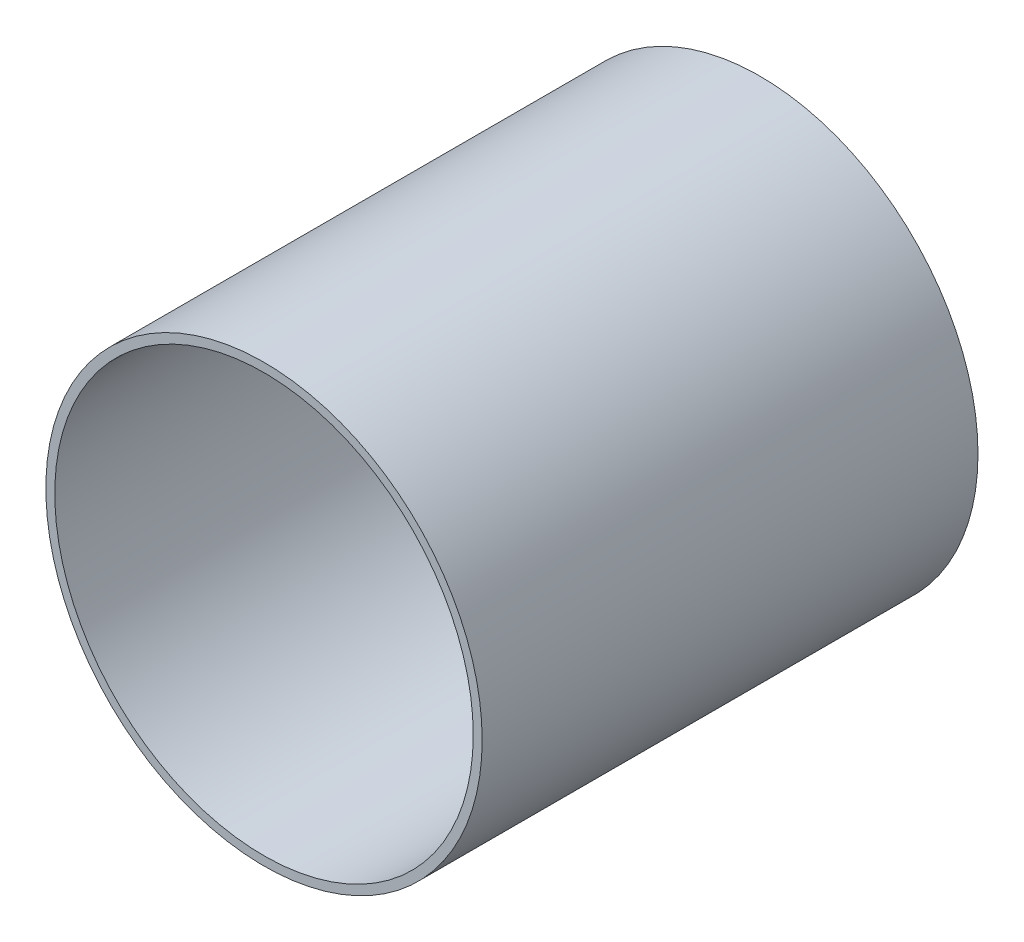
SolidWorks part; units mm, degrees
ref_plane "Front Plane" through (0, 0, 0) normal (0, 0, 1) x (1, 0, 0)
ref_plane "Top Plane" through (0, 0, 0) normal (0, 1, 0) x (1, 0, 0)
ref_plane "Right Plane" through (0, 0, 0) normal (1, 0, 0) x (0, 0, -1)
sketch "Sketch1" plane through (0, 0, 0) normal (0, 0, 1) x (1, 0, 0)
  circle A0 centre (0, 0) radius 10.55
  circle A1 centre (0, 0) radius 11
  dimension "D1" = 22
  dimension "D2" = 21.1
extrude "Boss-Extrude1" add sketch "Sketch1" along normal blind 25
